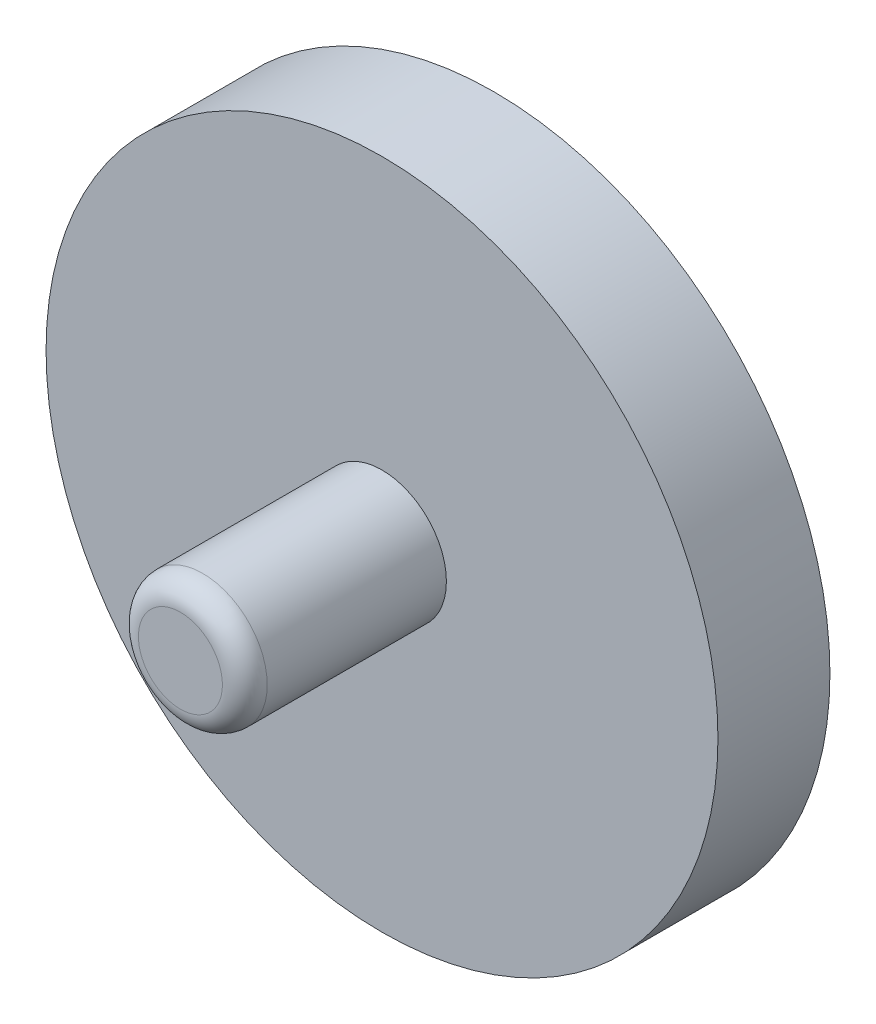
SolidWorks part; units mm, degrees
ref_plane "Front Plane" through (0, 0, 0) normal (0, 0, 1) x (1, 0, 0)
ref_plane "Top Plane" through (0, 0, 0) normal (0, 1, 0) x (1, 0, 0)
ref_plane "Right Plane" through (0, 0, 0) normal (1, 0, 0) x (0, 0, -1)
sketch "Sketch1" plane through (0, 0, 0) normal (0, 0, 1) x (1, 0, 0)
  circle A1 centre (0, 0) radius 7.5
  dimension "D1" = 15
extrude "Boss-Extrude1" add sketch "Sketch1" along normal blind 2.5 contours A1
sketch "Sketch2" plane through (0, 0, 2.5) normal (0, 0, 1) x (1, 0, 0)
  circle A0 centre (0, 0) radius 1.4375
extrude "Boss-Extrude2" add sketch "Sketch2" along normal blind 4.5
fillet "Fillet1" radius 0.5 1 edges at (1.4375, 0, 7)
